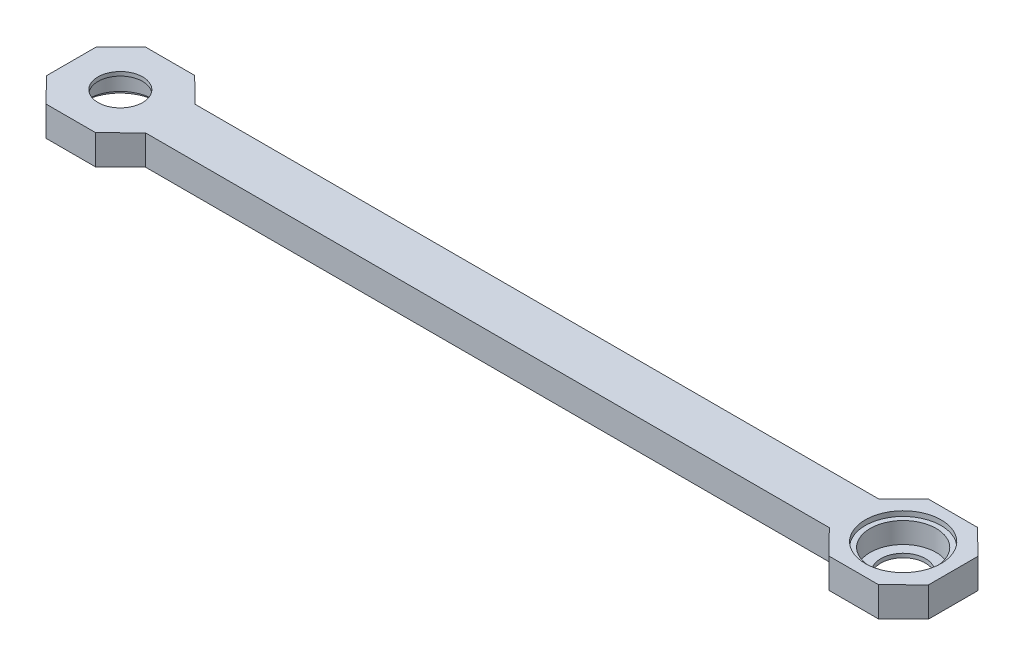
SolidWorks part; units mm, degrees
ref_plane "前视基准面" through (0, 0, 0) normal (0, 0, 1) x (1, 0, 0)
ref_plane "上视基准面" through (0, 0, 0) normal (0, 1, 0) x (1, 0, 0)
ref_plane "右视基准面" through (0, 0, 0) normal (1, 0, 0) x (0, 0, -1)
sketch "草图1" plane through (0, 0, 0) normal (0, 1, 0) x (1, 0, 0)
  line L0 (-56.1468, 0) -> (96.1142, 0) construction
  line L9 (-65.2623, 5) -> (-70.3633, 10)
  line L10 (-70.3633, 10) -> (-80.3633, 10)
  line L19 (-80.3633, 10) -> (-85.2623, 5)
  line L20 (-85.2623, 5) -> (-85.2623, -5)
  line L23 (72.7377, 5) -> (77.6367, 10)
  line L24 (77.6367, 10) -> (87.6367, 10)
  line L25 (87.6367, 10) -> (92.7398, 5)
  line L26 (92.7398, 5) -> (92.7398, -5)
  line L27 (-75.3633, 10) -> (-75.3633, -5.1974) construction
  line L28 (82.6367, 10) -> (82.6367, -7.8958) construction
  line L29 (-65.2623, -5) -> (-70.3633, -10)
  line L30 (-70.3633, -10) -> (-80.3633, -10)
  line L31 (-80.3633, -10) -> (-85.2623, -5)
  line L32 (87.6367, -10) -> (92.7398, -5)
  line L33 (77.6367, -10) -> (87.6367, -10)
  line L34 (72.7377, -5) -> (77.6367, -10)
  line L35 (-65.2623, 5) -> (72.7377, 5)
  line L36 (72.7377, -5) -> (-65.2623, -5)
  circle A0 centre (-75.3633, 0) radius 4.5
  circle A2 centre (82.6367, 0) radius 4.5
  point P18 (-27.2623, 0)
  point P24 (-85.2623, 0)
  point P25 (92.7398, 0)
  point P28 (72.7377, 0)
  dimension "D1" = 158
  dimension "D2" = 10
  dimension "D11" = 9
  dimension "D12" = 9
  dimension "D3" = 5
  dimension "D4" = 20.0021
  dimension "D5" = 10
  dimension "D6" = 7
  dimension "D7" = 10
  dimension "D8" = 7
  dimension "D9" = 10
  dimension "D10" = 5
  dimension "D13" = 20
extrude "凸台-拉伸1" add sketch "草图1" along normal blind 6
sketch "草图2" plane through (0, 6, 0) normal (0, 1, 0) x (1, 0, 0)
  circle A0 centre (82.6367, 0) radius 6.65
  dimension "D1" = 13.3
extrude "切除-拉伸1" cut sketch "草图2" against normal blind 5.2
sketch "草图3" plane through (0, 6, 0) normal (0, 1, 0) x (1, 0, 0)
  circle A0 centre (82.6367, 0) radius 7.65
  dimension "D1" = 15.3
extrude "切除-拉伸2" cut sketch "草图3" against normal blind 1
sketch "草图5" plane through (0, 0, 0) normal (0, -1, 0) x (1, 0, 0)
  circle A0 centre (-75.3633, 0) radius 6.65
  dimension "D1" = 13.3
extrude "切除-拉伸3" cut sketch "草图5" against normal blind 5.2
sketch "草图6" plane through (0, 0, 0) normal (0, -1, 0) x (1, 0, 0)
  circle A0 centre (-75.3633, 0) radius 7.65
  dimension "D1" = 15.3
extrude "切除-拉伸4" cut sketch "草图6" against normal blind 1
